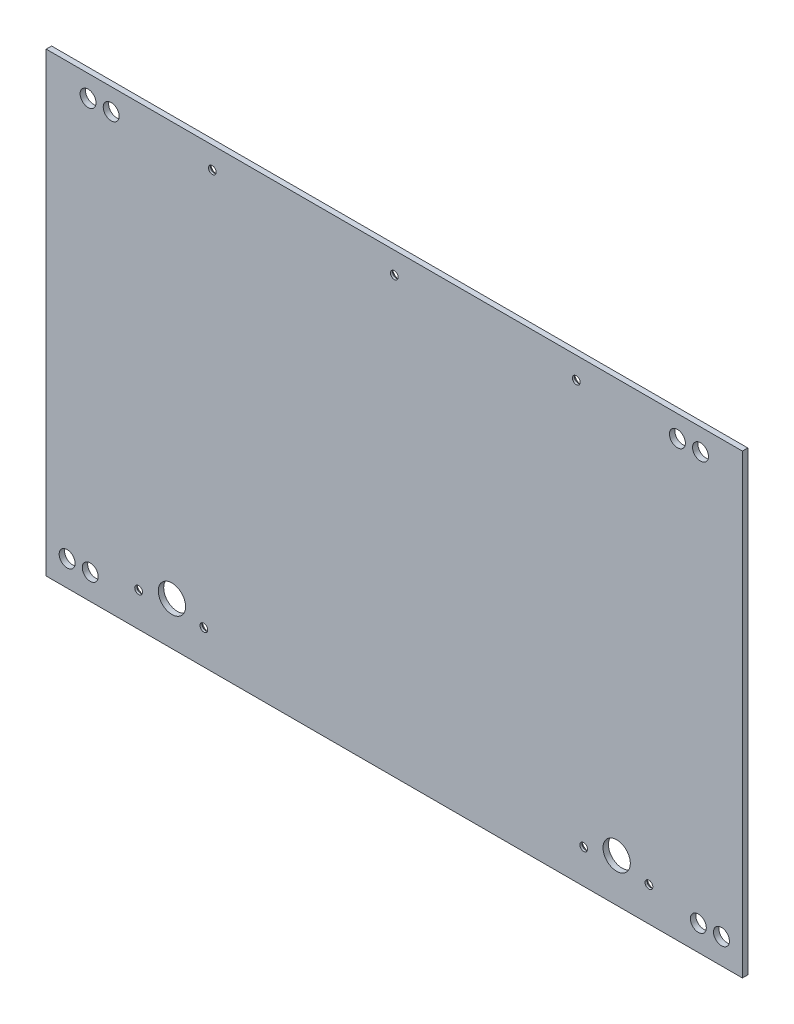
SolidWorks part; units mm, degrees
material "ABS"
ref_plane "X-Y Datum" through (0, 0, 0) normal (0, 0, 1) x (1, 0, 0)
ref_plane "X-Z Datum" through (0, 0, 0) normal (0, 1, 0) x (1, 0, 0)
ref_plane "Y-Z Datum" through (0, 0, 0) normal (1, 0, 0) x (0, 0, -1)
sketch "Sketch1" plane through (0, 0, 0) normal (0, 0, 1) x (1, 0, 0)
  line L0 (-153.025, 98.7125) -> (-153.025, -98.7125)
  line L1 (-153.025, 98.7125) -> (153.025, 98.7125)
  line L2 (-153.025, 98.7125) -> (-153.025, -98.7125)
  line L3 (-153.025, -98.7125) -> (153.025, -98.7125)
  line L4 (153.025, 98.7125) -> (153.025, -98.7125)
  line L5 (-153.025, 98.7125) -> (153.025, -98.7125) construction
  line L6 (-153.025, -98.7125) -> (153.025, 98.7125) construction
  line L7 (-153.025, -98.7125) -> (153.025, -98.7125)
  line L8 (153.025, 98.7125) -> (153.025, -98.7125)
  line L9 (-153.025, 98.7125) -> (153.025, 98.7125)
  circle A0 centre (-142.25, -87.9375) radius 10.775
  circle A1 centre (-118.25, -87.9375) radius 10.775 construction
  circle A2 centre (-130.25, -64.9375) radius 10.775
  point P0 (0, 0)
  dimension "D1" = 21.55
  dimension "D2" = 24
  dimension "D3" = 23
  dimension "D4" = 12
  dimension "D5" = 197.425
  dimension "D6" = 306.05
  dimension "D7" = 0
extrude "Boss-Extrude1" add sketch "Sketch1" along normal blind 2.3813 contours A0 L3 L4 L1 L2 A2 | A2 | A0 | A0 L2 L3 | L9 L0 L7 L8 L1 L4 L3 L2
sketch "Sketch9" plane through (0, 98.7125, 0) normal (0, 1, 0) x (1, 0, 0)
  line L4 (153.025, 0) -> (-153.025, 0)
  line L5 (-153.025, 0) -> (-153.025, -2.3813)
  line L6 (-153.025, -2.3813) -> (153.025, -2.3813)
  line L7 (153.025, -2.3813) -> (153.025, 0)
  line L8 (153.025, 0) -> (-153.025, 0)
  line L9 (-153.025, 0) -> (-153.025, -2.3813)
  line L10 (-153.025, -2.3813) -> (153.025, -2.3813)
  line L11 (153.025, -2.3813) -> (153.025, 0)
  dimension "D1" = 0
extrude "Boss-Extrude2" add sketch "Sketch9" along normal blind 3.175
sketch "Sketch10" plane through (0, 0, 0) normal (0, 0, -1) x (-1, 0, 0)
  circle A0 centre (-134.61, 92.3625) radius 3.5
  circle A1 centre (-124.45, 92.3625) radius 3.5
  circle A2 centre (-143.8175, -87.5375) radius 3.5
  circle A3 centre (-133.6575, -87.5375) radius 3.5
  point P1 (-133.6575, -87.5375)
  dimension "D1" = 7
extrude "Cut-Extrude1" cut sketch "Sketch10" against normal through all
mirror "Mirror1" about plane through (0, 0, 0) normal (1, 0, 0) of "Cut-Extrude1"
sketch "Sketch11" plane through (0, 0, 0) normal (0, 0, -1) x (-1, 0, 0)
  point P0 (-111.94, -83.7125)
  point P1 (-83.25, -83.7125)
  point P5 (-80, 92.3625)
  point P7 (0, 92.3625)
  point P9 (80, 92.3625)
  point P13 (112.402, -83.7125)
  point P15 (83.712, -83.7125)
hole_wizard "CSK for M3 Flat Head Machine Screw1" positions "Sketch11" profile "Sketch12" countersink size "M3" standard "ANSI Metric" end condition through all
sketch "Sketch12" plane through (111.94, -83.7125, 0) normal (1, 0, 0) x (0, 1, 0)
  line L0 (0, 0) -> (0, 2.3812)
  line L1 (0, 2.3812) -> (1.7, 2.3812)
  line L2 (1.7, 2.3812) -> (1.7, 1.45)
  line L3 (1.7, 1.45) -> (3.15, 0)
  line L5 (3.15, 0) -> (0, 0)
  line L6 (-1.7, 1.45) -> (-3.15, 0) construction
  line L11 (0, -6.35) -> (0, 107.95) construction
  dimension "Thru Hole Dia." = 3.4
  dimension "Thru Hole Depth" = 2.3813
  dimension "Near C'Sink Dia." = 6.3
  dimension "Near C'Sink Angle" = 90
sketch "Sketch13" plane through (0, 0, 0) normal (0, 0, -1) x (-1, 0, 0)
  circle A0 centre (-97.75, -79.7125) radius 6 construction
  circle A1 centre (97.75, -79.7125) radius 6 construction
  circle A2 centre (-97.75, -79.7125) radius 6
  circle A3 centre (97.75, -79.7125) radius 6
extrude "Cut-Extrude2" cut sketch "Sketch13" against normal through all
